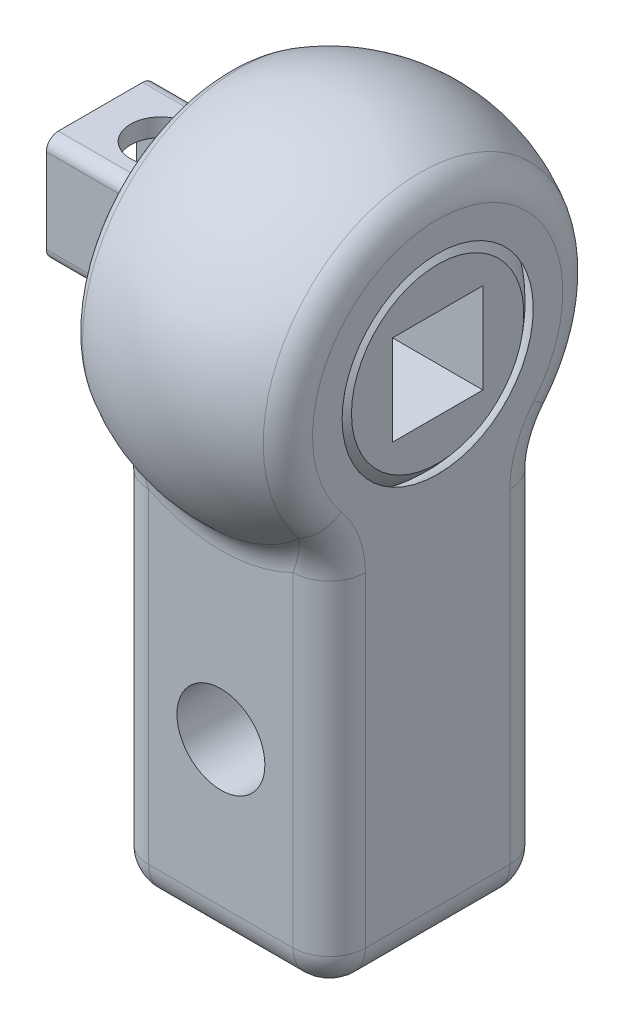
SolidWorks part; units mm, degrees
ref_plane "Alzado" through (0, 0, 0) normal (0, 0, 1) x (1, 0, 0)
ref_plane "Planta" through (0, 0, 0) normal (0, 1, 0) x (1, 0, 0)
ref_plane "Vista lateral" through (0, 0, 0) normal (1, 0, 0) x (0, 0, -1)
sketch "Croquis1" plane through (0, 0, 0) normal (0, 0, 1) x (1, 0, 0)
  line L0 (0, 0) -> (0, 30) construction
  line L1 (0, 27) -> (0, 30)
  line L2 (0, 30.5) -> (0, 42) construction
  line L3 (0, 30.5) -> (0, 53.5)
  line L4 (0, 54) -> (0, 57)
  arc A0 (0, 30.5) -> (0, 53.5) centre (0, 42) ccw
  arc A1 (0, 27) -> (0, 57) centre (0, 42) ccw
  arc A2 (0, 30) -> (0, 54) centre (0, 42) ccw
  dimension "D2" = 23
  dimension "D3" = 30
  dimension "D4" = 12
  dimension "D1" = 42
revolve "Revolución1" add sketch "Croquis1" angle 360 about L0
sketch "Croquis2" plane through (0, 0, 0) normal (0, 0, 1) x (1, 0, 0)
  line L0 (0, 0) -> (0, 42) construction
  line L1 (0, 42) -> (-9, 42) construction
  line L2 (-9, 42) -> (-9, 57)
  line L3 (-9, 57) -> (-19, 57)
  line L4 (-19, 57) -> (-19, 27)
  line L5 (-19, 27) -> (-9, 27)
  line L6 (-9, 27) -> (-9, 42)
  line L7 (-9, 42) -> (-15, 42) construction
  line L8 (19, 27) -> (9, 27)
  line L9 (19, 57) -> (19, 27)
  line L10 (9, 57) -> (19, 57)
  line L11 (9, 42) -> (9, 57)
  line L12 (9, 27) -> (9, 42)
  circle A0 centre (0, 42) radius 15 construction
  dimension "D1" = 42
  dimension "D2" = 6
  dimension "D3" = 30
  dimension "D4" = 10
extrude "Cortar-Extruir1" cut sketch "Croquis2" against normal through all both and the other way through all
sketch "Croquis3" plane through (0, 0, 0) normal (0, 1, 0) x (1, 0, 0)
  line L0 (9, -12) -> (9, 12) construction
  line L1 (-9, -9) -> (9, -9)
  line L2 (-9, -9) -> (-9, 9)
  line L3 (-9, 9) -> (9, 9)
  line L4 (9, -9) -> (9, 9)
  line L5 (-9, -9) -> (9, 9) construction
  line L6 (-9, 9) -> (9, -9) construction
  point P0 (0, 0)
  dimension "D1" = 18
  dimension "D2" = 18
extrude "Saliente-Extruir1" add sketch "Croquis3" along normal up to surface (34.0627 mm away)
sketch "Croquis4" plane through (-9, 0, 0) normal (-1, 0, 0) x (0, 0, 1)
  line L0 (-7.1589, 42) -> (7.1589, 42) construction
  line L2 (-3.75, 45.75) -> (3.75, 45.75)
  line L3 (-3.75, 45.75) -> (-3.75, 38.25)
  line L4 (-3.75, 38.25) -> (3.75, 38.25)
  line L5 (3.75, 45.75) -> (3.75, 38.25)
  line L6 (-3.75, 45.75) -> (3.75, 38.25) construction
  line L7 (-3.75, 38.25) -> (3.75, 45.75) construction
  circle A1 centre (0, 42) radius 7.1589 construction
  point P4 (0, 42)
  dimension "D1" = 7.5
  dimension "D2" = 7.5
extrude "Cortar-Extruir2" cut sketch "Croquis4" against normal through all both and the other way through all
sketch "Croquis5" plane through (-9, 0, 0) normal (-1, 0, 0) x (0, 0, 1)
  line L0 (-3.75, 42) -> (3.75, 42) construction
  line L1 (-3, 45) -> (3, 45)
  line L2 (-3, 45) -> (-3, 39)
  line L3 (-3, 39) -> (3, 39)
  line L4 (3, 45) -> (3, 39)
  line L5 (-3, 45) -> (3, 39) construction
  line L6 (-3, 39) -> (3, 45) construction
  line L7 (-3.75, 38.25) -> (-3.75, 45.75) construction
  line L8 (-4.5, 46.5) -> (4.5, 46.5)
  line L9 (-4.5, 46.5) -> (-4.5, 37.5)
  line L10 (-4.5, 37.5) -> (4.5, 37.5)
  line L11 (4.5, 46.5) -> (4.5, 37.5)
  line L12 (-4.5, 46.5) -> (4.5, 37.5) construction
  line L13 (-4.5, 37.5) -> (4.5, 46.5) construction
  point P0 (0, 42)
  point P10 (0, 42)
  point P16 (0, 42)
  dimension "D1" = 6
  dimension "D2" = 1.5
  dimension "D3" = 1.5
extrude "Saliente-Extruir2" add sketch "Croquis5" along normal blind 10
sketch "Croquis7" plane through (0, 0, 9) normal (0, 0, 1) x (1, 0, 0)
  line L0 (0, 0) -> (0, 15) construction
  circle A0 centre (0, 15) radius 3.65
  dimension "D2" = 7.3
  dimension "D1" = 15
extrude "Cortar-Extruir3" cut sketch "Croquis7" against normal through all both and the other way through all
fillet "Redondeo1" radius 3 12 edges at (9, 54, 0) (-9, 54, 0) (0, 30, 9) (-9, 17.0314, 9) (0, 0, 9) (-9, 17.0314, -9) (-9, 0, 0) (0, 30, -9) (9, 17.0314, -9) (0, 0, -9) (9, 17.0314, 9) (9, 0, 0)
sketch "Croquis8" plane through (0, 46.5, 0) normal (0, 1, 0) x (1, 0, 0)
  line L0 (-19, 0) -> (-9, 0) construction
  line L1 (-19, -4.5) -> (-19, 4.5) construction
  line L2 (-9, -4.5) -> (-9, 4.5) construction
  circle A0 centre (-14, 0) radius 2.5
  dimension "D1" = 5
extrude "Cortar-Extruir4" cut sketch "Croquis8" against normal blind 10
fillet "Redondeo2" radius 1 4 edges at (-14, 37.5, 4.5) (-14, 37.5, -4.5) (-14, 46.5, -4.5) (-14, 46.5, 4.5)
fillet "Redondeo3" radius 0.5 8 edges at (-9, 37.7929, -4.2071) (-9, 42, -4.5) (-9, 46.2071, -4.2071) (-9, 46.5, 0) (-9, 46.2071, 4.2071) (-9, 42, 4.5) (-9, 37.7929, 4.2071) (-9, 37.5, 0)
